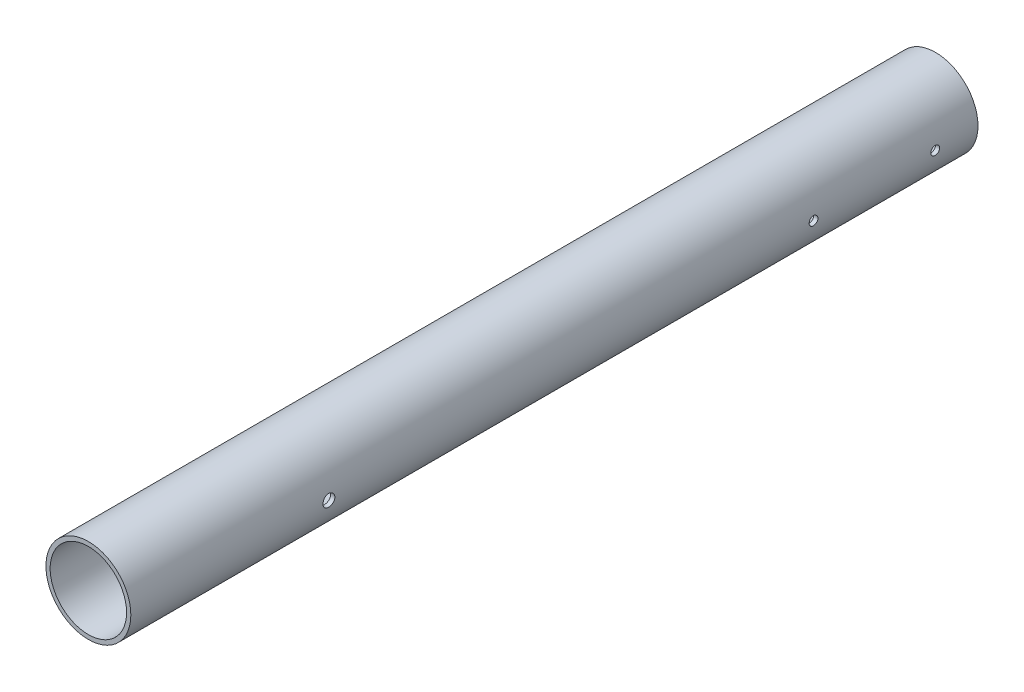
SolidWorks part; units mm, degrees
material "Hexcel AS4C (3000 丝)"
ref_plane "前视基准面" through (0, 0, 0) normal (0, 0, 1) x (1, 0, 0)
ref_plane "上视基准面" through (0, 0, 0) normal (0, 1, 0) x (1, 0, 0)
ref_plane "右视基准面" through (0, 0, 0) normal (1, 0, 0) x (0, 0, -1)
sketch "草图1" plane through (0, 0, 0) normal (0, 0, 1) x (1, 0, 0)
  circle A0 centre (0, 0) radius 15
  circle A1 centre (0, 0) radius 13.5
  dimension "D1" = 30
  dimension "D2" = 27
extrude "凸台-拉伸1" add sketch "草图1" along normal blind 299.33
sketch "草图2" plane through (0, 0, 0) normal (1, 0, 0) x (0, 0, -1)
  line L0 (0, 0) -> (-299.33, 0) construction
  line L1 (-299.33, 15) -> (-299.33, -15) construction
  line L2 (0, -13.5) -> (0, 13.5) construction
  circle A0 centre (-15.1, 0) radius 1.55
  circle A1 centre (-58.1, 0) radius 1.55
  dimension "D1" = 3.1
  dimension "D2" = 15.1
  dimension "D3" = 3.1
  dimension "D4" = 43
extrude "切除-拉伸1" cut sketch "草图2" against normal through all both and the other way through all
sketch "草图3" plane through (0, 0, 0) normal (1, 0, 0) x (0, 0, -1)
  line L0 (-299.33, 0) -> (0, 0) construction
  line L1 (-299.33, 15) -> (-299.33, -15) construction
  circle A0 centre (-229.33, 0) radius 2.1
  dimension "D1" = 4.2
  dimension "D2" = 70
extrude "切除-拉伸2" cut sketch "草图3" against normal through all both and the other way through all
